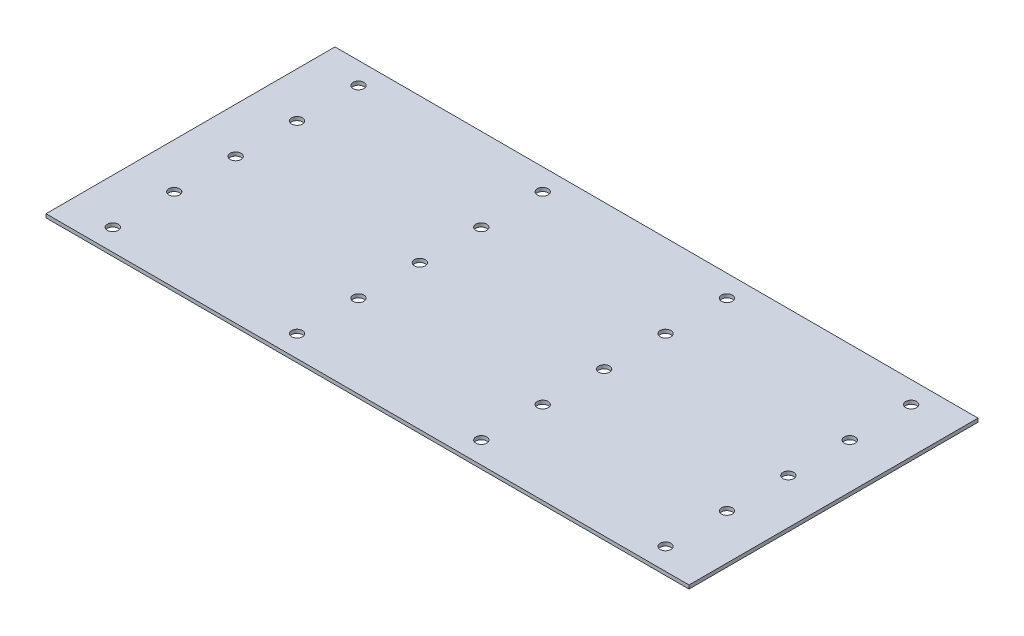
SolidWorks part; units mm, degrees
ref_plane "Front Plane" through (0, 0, 0) normal (0, 0, 1) x (1, 0, 0)
ref_plane "Top Plane" through (0, 0, 0) normal (0, 1, 0) x (1, 0, 0)
ref_plane "Right Plane" through (0, 0, 0) normal (1, 0, 0) x (0, 0, -1)
sketch "Sketch1" plane through (0, 0, 0) normal (0, 1, 0) x (1, 0, 0)
  line L1 (-89, -40) -> (89, -40)
  line L2 (-89, -40) -> (-89, 40)
  line L3 (-89, 40) -> (89, 40)
  line L4 (89, -40) -> (89, 40)
  line L5 (-89, -40) -> (89, 40) construction
  line L6 (-89, 40) -> (89, -40) construction
  point P0 (0, 0)
  dimension "D1" = 178
  dimension "D2" = 80
extrude "Boss-Extrude1" add sketch "Sketch1" along normal blind 1
sketch "Sketch2" plane through (0, 1, 0) normal (0, 1, 0) x (1, 0, 0)
  line L0 (-89, 40) -> (-89, -40) construction
  line L3 (89, -40) -> (89, 40) construction
  circle A0 centre (-76.5, 34) radius 1.5
  circle A2 centre (-76.5, 17) radius 1.5
  circle A3 centre (-76.5, 0) radius 1.5
  circle A4 centre (-76.5, -17) radius 1.5
  circle A5 centre (-76.5, -34) radius 1.5
  circle A6 centre (-25.5, 34) radius 1.5
  circle A7 centre (-25.5, 17) radius 1.5
  circle A8 centre (-25.5, 0) radius 1.5
  circle A9 centre (-25.5, -17) radius 1.5
  circle A10 centre (-25.5, -34) radius 1.5
  circle A11 centre (25.5, 34) radius 1.5
  circle A12 centre (25.5, 17) radius 1.5
  circle A13 centre (25.5, 0) radius 1.5
  circle A14 centre (25.5, -17) radius 1.5
  circle A15 centre (25.5, -34) radius 1.5
  circle A16 centre (76.5, 34) radius 1.5
  circle A17 centre (76.5, 17) radius 1.5
  circle A18 centre (76.5, 0) radius 1.5
  circle A19 centre (76.5, -17) radius 1.5
  circle A20 centre (76.5, -34) radius 1.5
  point P11 (0, 0)
  dimension "D1" = 3
  dimension "D2" = 17
  dimension "D3" = 17
  dimension "D4" = 17
  dimension "D5" = 17
  dimension "D6" = 4
  dimension "6" = 12.5
  dimension "D7" = 12.5
extrude "Cut-Extrude1" cut sketch "Sketch2" against normal blind 1
